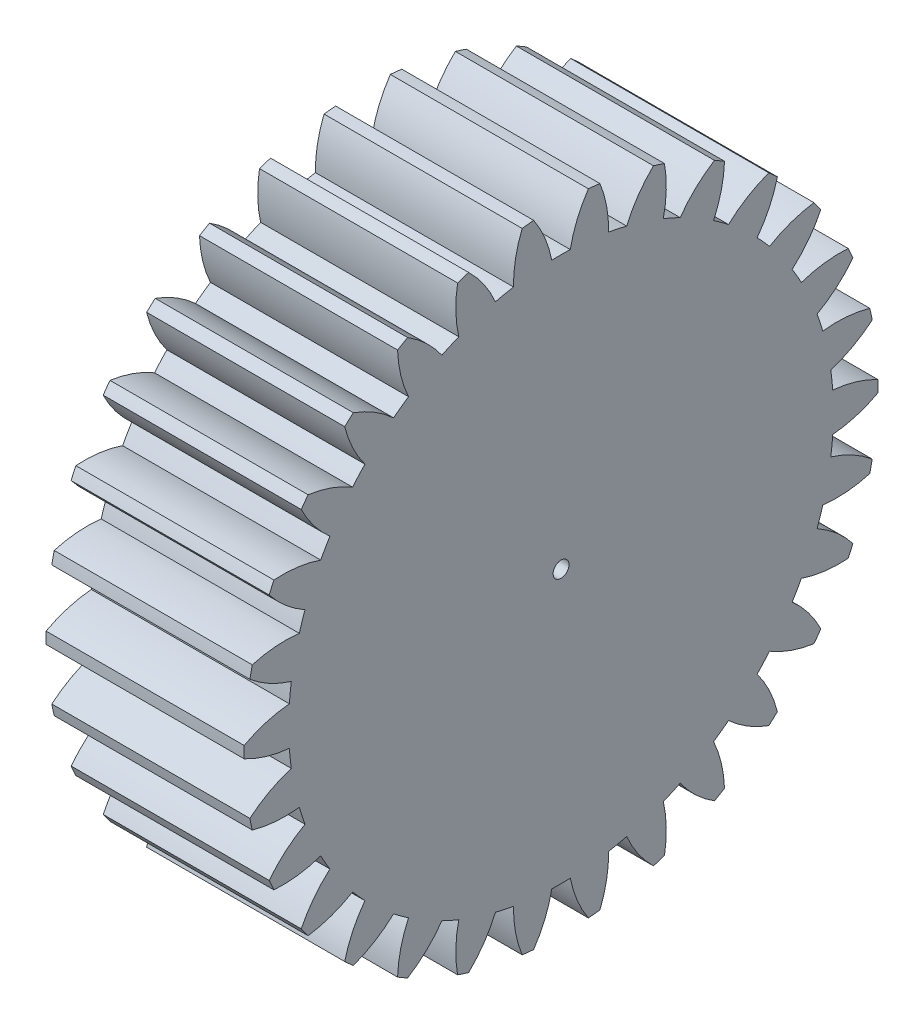
SolidWorks part; units mm, degrees
ref_plane "Plane1" through (0, 0, 0) normal (0, 0, 1) x (1, 0, 0)
ref_plane "Plane2" through (0, 0, 0) normal (0, 1, 0) x (1, 0, 0)
ref_plane "Plane3" through (0, 0, 0) normal (1, 0, 0) x (0, 0, -1)
sketch "HoldingSke" plane through (0, 0, 0) normal (0, 1, 0) x (1, 0, 0)
  line L0 (0, 0) -> (0.866, -0.5)
  line L1 (-15, 0) -> (100, 0) construction
  line L2 (0, 0) -> (-2.1039, 2.3779)
  line L3 (0, 0) -> (-11.863, 4.5341)
  line L4 (0, 0) -> (7.479, 4.318)
  line L5 (0, 0) -> (-46.8476, -17.4728)
  line L6 (0, 0) -> (-8.2896, -5.593)
  line L7 (-2.1039, 2.3779) -> (8.6586, 51.2059)
  line L8 (-76.2, 54.61) -> (-76.1, 54.61)
  line L9 (-71.009, 38.7566) -> (-53.1078, 45.2721)
  line L10 (-76.2, 71.12) -> (104.1128, 71.12)
  line L11 (0, 0) -> (-10, 0)
  line L12 (-76.2, 101.6) -> (-76.162, 101.6)
  line L13 (24.9733, 27.94) -> (52.9518, 28.4284)
  line L14 (24.9733, 27.94) -> (24.9743, 27.94)
  line L15 (24.9733, 27.94) -> (100.4006, 29.5858)
  line L16 (-63.627, -1) -> (-12.827, -1)
  circle A0 centre (0, 0) radius 0.4
  circle A1 centre (0, 0) radius 13.749
  circle A2 centre (0, 0) radius 37.5
  circle A3 centre (0, 0) radius 0.4
  dimension "MHD" = 27.498
  dimension "Hub_dia" = 75
  dimension "Bore" = 0.8
  dimension "MBD" = 0.8
  dimension "Num_teeth" = 30
  dimension "Pitch" = 1
  dimension "Overall_len" = 50
  dimension "Show_teeth" = 30
  dimension "Thickness" = 10
  dimension "OAL" = 50.0001
  dimension "T_dim" = 0.1
  dimension "Ap" = 20
  dimension "H" = 19.05
  dimension "Pitch_radius" = 180.3128
  dimension "Width" = 10
  dimension "Backlash" = 0.038
  dimension "Addendum_fac" = 1
  dimension "Dedendum_fac" = 1.25
  dimension "Clearance_fac" = 0.25
  dimension "Dedendum_add" = 0.001
  dimension "Module" = 1
sketch "BasProSke" plane through (0, 0, 0) normal (0, 1, 0) x (1, 0, 0)
  line L0 (-10, 0) -> (60, 0) construction
  line L1 (0, 0) -> (0, 16)
  line L2 (0, 0) -> (10, 0)
  line L3 (10, 0) -> (10, 16)
  line L4 (10, 16) -> (0, 16)
  dimension "Thickness" = 10
  dimension "Diameter" = 32
revolve "Base-Revolve" add sketch "BasProSke" angle 360 about L0
sketch "TooCutSke" plane through (0, 0, 0) normal (1, 0, 0) x (0, 0, -1)
  line L1 (0, 0) -> (0, 107) construction
  line L2 (0, 0) -> (-0.8515, 14.9758) construction
  line L3 (0, 0) -> (-3.1323, 29.8014) construction
  line L4 (-0.8515, 14.9758) -> (-1.5661, 14.9007) construction
  arc A0 (0.4664, 13.7411) -> (-0.4664, 13.7411) centre (0, 0) ccw
  arc A1 (1.3975, 15.9644) -> (-1.3975, 15.9644) centre (0, 0) ccw
  circle A2 centre (0, 0) radius 15 construction
  circle A3 centre (0, 0) radius 14.0954 construction
  arc A4 (-0.4664, 13.7411) -> (-1.3975, 15.9644) centre (-6.3534, 12.5823) ccw
  arc A5 (1.3975, 15.9644) -> (0.4664, 13.7411) centre (6.3534, 12.5823) ccw
  dimension "Root_dia" = 27.498
  dimension "Overcut_dia" = 32.0508
  dimension "Pitch_dia" = 30
  dimension "Base_dia" = 28.1908
  dimension "Flank_rad" = 6
  dimension "Half_ang" = 6
  dimension "Half_CT" = 0.7185
extrude "ToothCut" cut sketch "TooCutSke" along normal through all
fillet "Breaks" [suppressed] radius 0.02
fillet "RootFillets" [suppressed] radius 0.251
pattern_circular "TeethCuts" count 30 every 12 about axis through (-10, 0, 0) along (1, 0, 0) of "ToothCut", "RootFillets", "Breaks"
sketch "HubNeaOneSke" plane through (0, 0, 0) normal (-1, 0, 0) x (0, 0, 1)
  circle A0 centre (0, 0) radius 13.749
  dimension "Diameter" = 27.498
extrude "HubNearOne" [suppressed] add sketch "HubNeaOneSke" along normal blind 40.0001
sketch "HubNeaBotSke" plane through (0, 0, 0) normal (-1, 0, 0) x (0, 0, 1)
  circle A0 centre (0, 0) radius 13.749
  dimension "Diameter" = 27.498
extrude "HubNearBoth" [suppressed] add sketch "HubNeaBotSke" along normal blind 20
ref_plane "FarPln" through (10, 0, 0) normal (1, 0, 0) x (0, 0, -1)
sketch "HubFarSke" plane through (10, 0, 0) normal (1, 0, 0) x (0, 0, -1)
  circle A0 centre (0, 0) radius 13.749
  dimension "Diameter" = 27.498
extrude "HubFar" [suppressed] add sketch "HubFarSke" along normal blind 20
sketch "BorSke" plane through (0, 0, 0) normal (1, 0, 0) x (0, 0, -1)
  circle A0 centre (0, 0) radius 0.4
  dimension "Diameter" = 0.8
extrude "Bore" cut sketch "BorSke" along normal mid plane 100.0001
sketch "KeySke" plane through (0, 0, 0) normal (1, 0, 0) x (0, 0, -1)
  line L0 (-0.05, 0) -> (-0.05, 0.5)
  line L1 (-0.05, 0.5) -> (0.05, 0.5)
  line L2 (0.05, 0.5) -> (0.05, 0)
  line L3 (0, 0) -> (0, 34) construction
  line L4 (-0.05, 0) -> (0.05, 0)
  dimension "Offset" = 0.5
  dimension "Width" = 0.1
extrude "Keyway" [suppressed] cut sketch "KeySke" along normal mid plane 100.0001
pattern_circular "Keyway2" [suppressed] count 2 every 90 about axis through (-10, 0, 0) along (1, 0, 0)
equation "' \"Module@HoldingSke\" = 6.35"
equation "' \"Num_teeth@HoldingSke\" = 12"
equation "' \"Ap@HoldingSke\" =  20"
equation "' \"Ap@HoldingSke\" = 20"
equation "' \"Width@HoldingSke\" = 0.5 * 25.4"
equation "' \"Hub_dia@HoldingSke\"= 1 * 25.4"
equation "' \"Hub_dia@HoldingSke\" = 1 * 25.4"
equation "' \"Overall_len@HoldingSke\" = 1.0 * 25.4"
equation "' \"Bore@HoldingSke\" = 0.75 * 25.4"
equation "' \"T_dim@HoldingSke\" = 0.1 * 25.4"
equation "' \"Width@KeySke\" = 0.25 * 25.4"
equation "' \"Show_teeth@HoldingSke\" = 13"
equation "' \"Backlash@HoldingSke\" = 0.009 * 25.4"
equation "' \"Addendum_fac@HoldingSke\" = 1.0"
equation "' \"Dedendum_fac@HoldingSke\" = 1.25"
equation "' \"Dedendum_add@HoldingSke\" = 0.00005 * 25.4"
equation "' \"Clearance_fac@HoldingSke\" = 0.25"
equation "\"Pitch@HoldingSke\" = 1 / \"Module@HoldingSke\""
equation "\"Overcut_dia@TooCutSke\" = (\"Num_teeth@HoldingSke\" + 2 * \"Addendum_fac@HoldingSke\") / \"Pitch@HoldingSke\" + 0.002 * 25.4"
equation "\"Pitch_dia@TooCutSke\" = \"Num_teeth@HoldingSke\" / \"Pitch@HoldingSke\""
equation "\"Base_dia@TooCutSke\" = \"Num_teeth@HoldingSke\" / \"Pitch@HoldingSke\" * cos((\"Ap@HoldingSke\"  * 3.14159265 / 180))"
equation "\"Root_dia@TooCutSke\" = (\"Num_teeth@HoldingSke\" + 2) / \"Pitch@HoldingSke\" - 2 * (\"Addendum_fac@HoldingSke\" + \"Dedendum_fac@HoldingSke\") / \"Pitch@HoldingSke\" - \"Dedendum_add@HoldingSke\" * 2"
equation "\"Half_ang@TooCutSke\" = 180 / \"Num_teeth@HoldingSke\""
equation "\"Half_CT@TooCutSke\" = \"Num_teeth@HoldingSke\" / \"Pitch@HoldingSke\" * sin((3.14159265 / 2 / \"Num_teeth@HoldingSke\")) / 2 - 7 * \"Backlash@HoldingSke\" / 4"
equation "\"Flank_rad@TooCutSke\" = \"Num_teeth@HoldingSke\" / \"Pitch@HoldingSke\" / 5"
equation "\"Radius@RootFillets\" = \"Clearance_fac@HoldingSke\" / \"Pitch@HoldingSke\" + \"Dedendum_add@HoldingSke\""
equation "\"Break_rad@Breaks\" = 0.02 / \"Pitch@HoldingSke\""
equation "\"Thickness@HoldingSke\" = \"Width@HoldingSke\""
equation "\"OAL@HoldingSke\" = \"Thickness@HoldingSke\""
equation "\"MHD@HoldingSke\" = (\"Num_teeth@HoldingSke\" + 2) / \"Pitch@HoldingSke\" - 2 * (\"Addendum_fac@HoldingSke\" + \"Dedendum_fac@HoldingSke\")  / \"Pitch@HoldingSke\" - \"Dedendum_add@HoldingSke\" * 2"
equation "\"MBD@HoldingSke\" = (\"Num_teeth@HoldingSke\" + 2) / \"Pitch@HoldingSke\" - 2 * (\"Addendum_fac@HoldingSke\" + \"Dedendum_fac@HoldingSke\")  / \"Pitch@HoldingSke\" - \"Dedendum_add@HoldingSke\" * 2 - 0.002 * 25.4"
equation "\"MHD@HoldingSke\" = ((sgn( \"MHD@HoldingSke\" - \"Hub_dia@HoldingSke\" )-1)*( \"MHD@HoldingSke\" - \"Hub_dia@HoldingSke\" ))/-2+ \"Hub_dia@HoldingSke\""
equation "\"MBD@HoldingSke\" = ((sgn( \"MBD@HoldingSke\" - \"Bore@HoldingSke\" )-1)*( \"MBD@HoldingSke\" - \"Bore@HoldingSke\" ))/-2+ \"Bore@HoldingSke\""
equation "\"OAL@HoldingSke\" = ((sgn( \"OAL@HoldingSke\" - \"Overall_len@HoldingSke\" )+1)*( \"OAL@HoldingSke\" - \"Overall_len@HoldingSke\" ))/2 + \"Overall_len@HoldingSke\" + 0.000002 * 25.4"
equation "\"Num_teeth@TeethCuts\" = int( \"Show_teeth@HoldingSke\" ) + 1"
equation "\"Num_teeth@TeethCuts\" = ((sgn( \"Num_teeth@TeethCuts\" - \"Num_teeth@HoldingSke\" )-1)*( \"Num_teeth@TeethCuts\" - \"Num_teeth@HoldingSke\" ))/-2+ \"Num_teeth@HoldingSke\""
equation "\"Num_teeth@TeethCuts\" = ((sgn( \"Num_teeth@TeethCuts\" - 2.0)+1)*( \"Num_teeth@TeethCuts\" - 2.0))/2 +2.0"
equation "\"Angle@TeethCuts\" = 360.0 / \"Num_teeth@HoldingSke\""
equation "\"Diameter@BasProSke\" = (\"Num_teeth@HoldingSke\" + 2 * \"Addendum_fac@HoldingSke\") / \"Pitch@HoldingSke\""
equation "\"Thickness@BasProSke\"  = \"Thickness@HoldingSke\""
equation "' \"Fillet_rad@BasProSke\" =  \"Thickness@HoldingSke\" * 0.05"
equation "' \"Fillet_rad@BasProSke\" = \"Thickness@HoldingSke\" * 0.05"
equation "\"MHD@HoldingSke\" = ((sgn( \"MHD@HoldingSke\" - \"Root_dia@TooCutSke\" )-1)*( \"MHD@HoldingSke\" - \"Root_dia@TooCutSke\" ))/-2+ \"Root_dia@TooCutSke\""
equation "\"Diameter@HubNeaOneSke\" = \"MHD@HoldingSke\""
equation "\"Length@HubNearOne\" = \"OAL@HoldingSke\" - \"Thickness@BasProSke\""
equation "\"Diameter@HubNeaBotSke\" = \"MHD@HoldingSke\""
equation "\"Length@HubNearBoth\" = ( \"OAL@HoldingSke\" - \"Thickness@BasProSke\" ) / 2.0"
equation "\"Thickness@FarPln\" = \"Thickness@BasProSke\""
equation "\"Diameter@HubFarSke\" = \"MHD@HoldingSke\""
equation "\"Length@HubFar\" = ( \"OAL@HoldingSke\" - \"Thickness@BasProSke\" ) / 2.0"
equation "\"Diameter@BorSke\" = \"MBD@HoldingSke\""
equation "\"D1@Bore\" = \"OAL@HoldingSke\" * 2.0"
equation "\"D1@Keyway\" = \"OAL@HoldingSke\" * 2.0"
equation "\"Offset@KeySke\" = \"T_dim@HoldingSke\" + \"MBD@HoldingSke\" / 2.0"
